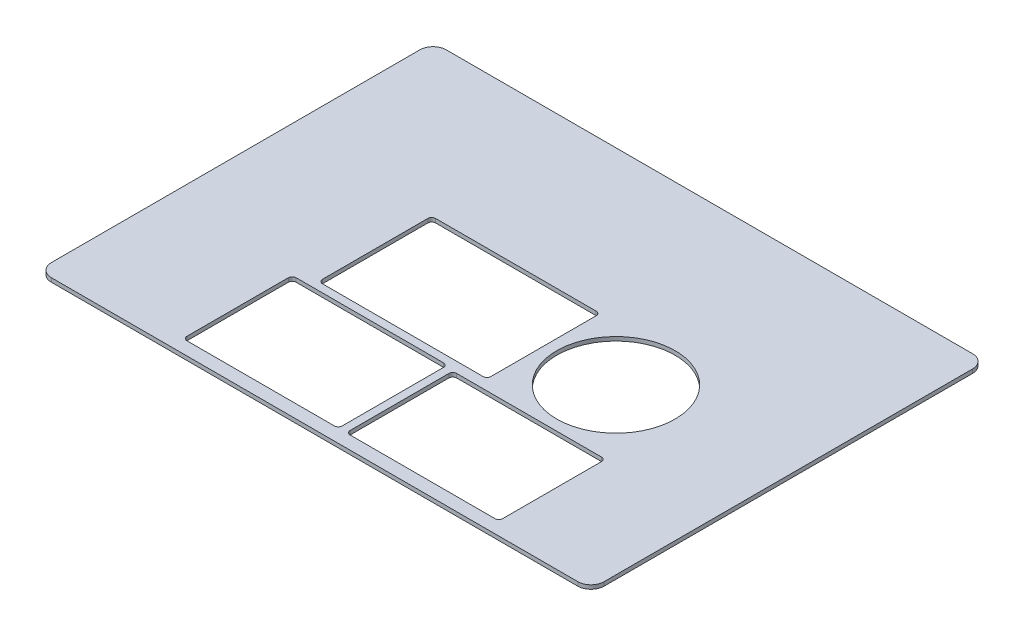
SolidWorks part; units mm, degrees
ref_plane "前视基准面" through (0, 0, 0) normal (0, 0, 1) x (1, 0, 0)
ref_plane "上视基准面" through (0, 0, 0) normal (0, 1, 0) x (1, 0, 0)
ref_plane "右视基准面" through (0, 0, 0) normal (1, 0, 0) x (0, 0, -1)
sketch "草图2" plane through (0, 0, 0) normal (0, 1, 0) x (1, 0, 0)
  line L1 (-210, -150) -> (210, -150)
  line L2 (-210, -150) -> (-210, 150)
  line L3 (-210, 150) -> (210, 150)
  line L4 (210, -150) -> (210, 150)
  line L5 (-210, -150) -> (210, 150) construction
  line L6 (-210, 150) -> (210, -150) construction
  line L7 (14, -140) -> (130, -140)
  line L8 (14, -140) -> (14, -59)
  line L9 (14, -59) -> (130, -59)
  line L10 (130, -140) -> (130, -59)
  line L11 (14, -140) -> (130, -59) construction
  line L12 (14, -59) -> (130, -140) construction
  line L13 (-110, -140) -> (8, -140)
  line L14 (-110, -140) -> (-110, -57)
  line L15 (-110, -57) -> (8, -57)
  line L16 (8, -140) -> (8, -57)
  line L17 (-110, -140) -> (8, -57) construction
  line L18 (-110, -57) -> (8, -140) construction
  line L19 (-96, -51) -> (32, -51)
  line L20 (-96, -51) -> (-96, 35)
  line L21 (-96, 35) -> (32, 35)
  line L22 (32, -51) -> (32, 35)
  line L23 (-96, -51) -> (32, 35) construction
  line L24 (-96, 35) -> (32, -51) construction
  circle A0 centre (85, -6) radius 45
  point P0 (0, 0)
  point P5 (72, -99.5)
  point P11 (-51, -98.5)
  point P18 (-32, -8)
  dimension "D7" = 90
  dimension "D13" = 8
  dimension "D14" = 80
  dimension "D17" = 8
  dimension "D1" = 420
  dimension "D2" = 300
  dimension "D3" = 116
  dimension "D4" = 81
  dimension "D5" = 118
  dimension "D6" = 83
  dimension "D8" = 128
  dimension "D9" = 86
  dimension "D10" = 80
  dimension "D11" = 6
  dimension "D12" = 10
  dimension "D15" = 6
  dimension "D16" = 10
extrude "凸台-拉伸2" add sketch "草图2" along normal blind 3
fillet "圆角1" radius 3 1 edges at (-96, 1.5, -35)
fillet "圆角2" radius 3 1 edges at (-96, 1.5, 51)
fillet "圆角3" radius 3 1 edges at (32, 1.5, 51)
fillet "圆角4" radius 3 1 edges at (32, 1.5, -35)
fillet "圆角5" radius 3 1 edges at (14, 1.5, 140)
fillet "圆角6" radius 3 1 edges at (14, 1.5, 59)
fillet "圆角7" radius 3 1 edges at (130, 1.5, 59)
fillet "圆角8" radius 3 1 edges at (130, 1.5, 140)
fillet "圆角9" radius 3 1 edges at (8, 1.5, 140)
fillet "圆角10" radius 3 1 edges at (8, 1.5, 57)
fillet "圆角11" radius 3 1 edges at (-110, 1.5, 140)
fillet "圆角12" radius 3 1 edges at (-110, 1.5, 57)
fillet "圆角13" radius 10 1 edges at (-210, 1.5, 150)
fillet "圆角14" radius 10 1 edges at (210, 1.5, 150)
fillet "圆角15" radius 10 1 edges at (210, 1.5, -150)
fillet "圆角16" radius 10 1 edges at (-210, 1.5, -150)
